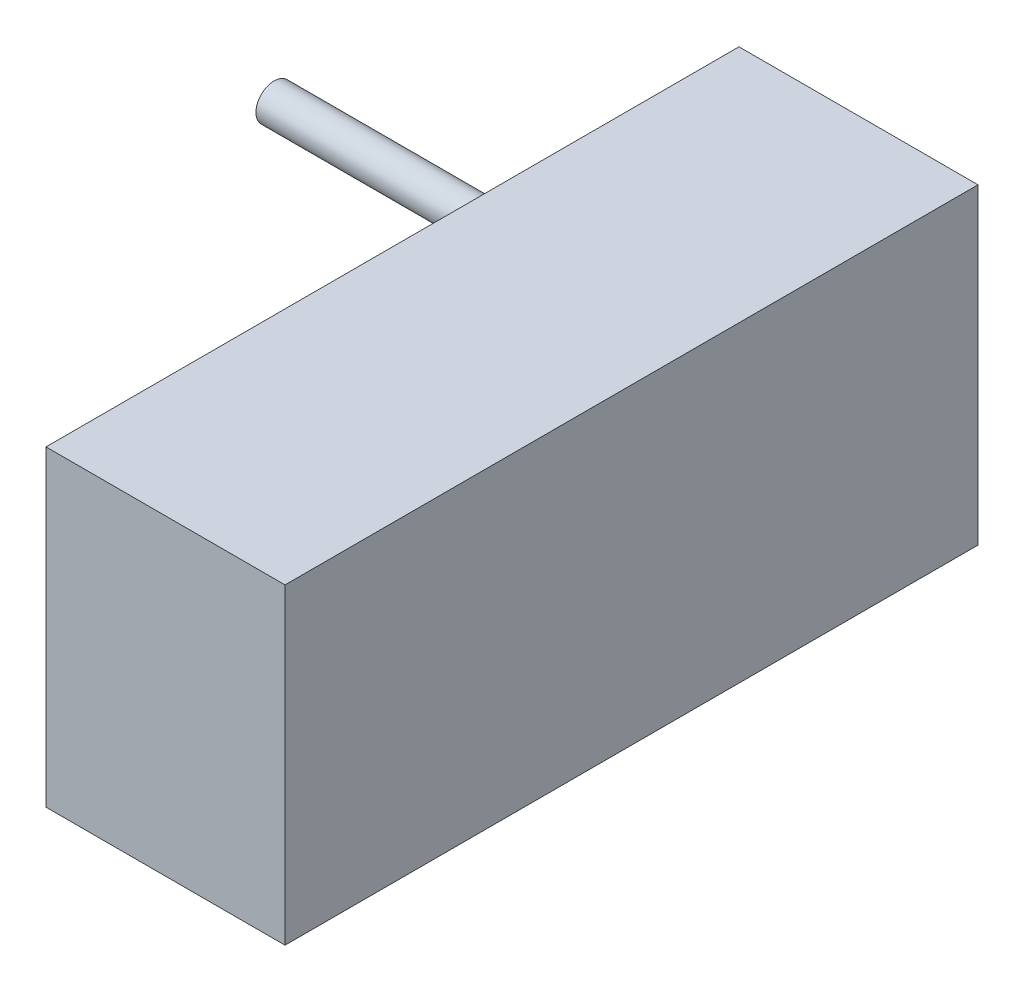
SolidWorks part; units mm, degrees
ref_plane "Plan de face" through (0, 0, 0) normal (0, 0, 1) x (1, 0, 0)
ref_plane "Plan de dessus" through (0, 0, 0) normal (0, 1, 0) x (1, 0, 0)
ref_plane "Plan de droite" through (0, 0, 0) normal (1, 0, 0) x (0, 0, -1)
sketch "Esquisse1" plane through (0, 0, 0) normal (0, 1, 0) x (1, 0, 0)
  line L0 (0, 0) -> (19.15, 0)
  line L1 (0, 0) -> (0, 55.52)
  line L2 (0, 55.52) -> (19.15, 55.52)
  line L3 (19.15, 55.52) -> (19.15, 0)
extrude "Boss.-Extru.1" add sketch "Esquisse1" along normal blind 25 contours L1 L2 L3 L0
sketch "Esquisse3" plane through (0, 0, 0) normal (1, 0, 0) x (0, 0, -1)
  circle A0 centre (45.58, 12.5) radius 1.46
extrude "Boss.-Extru.2" add sketch "Esquisse3" against normal blind 27.3
